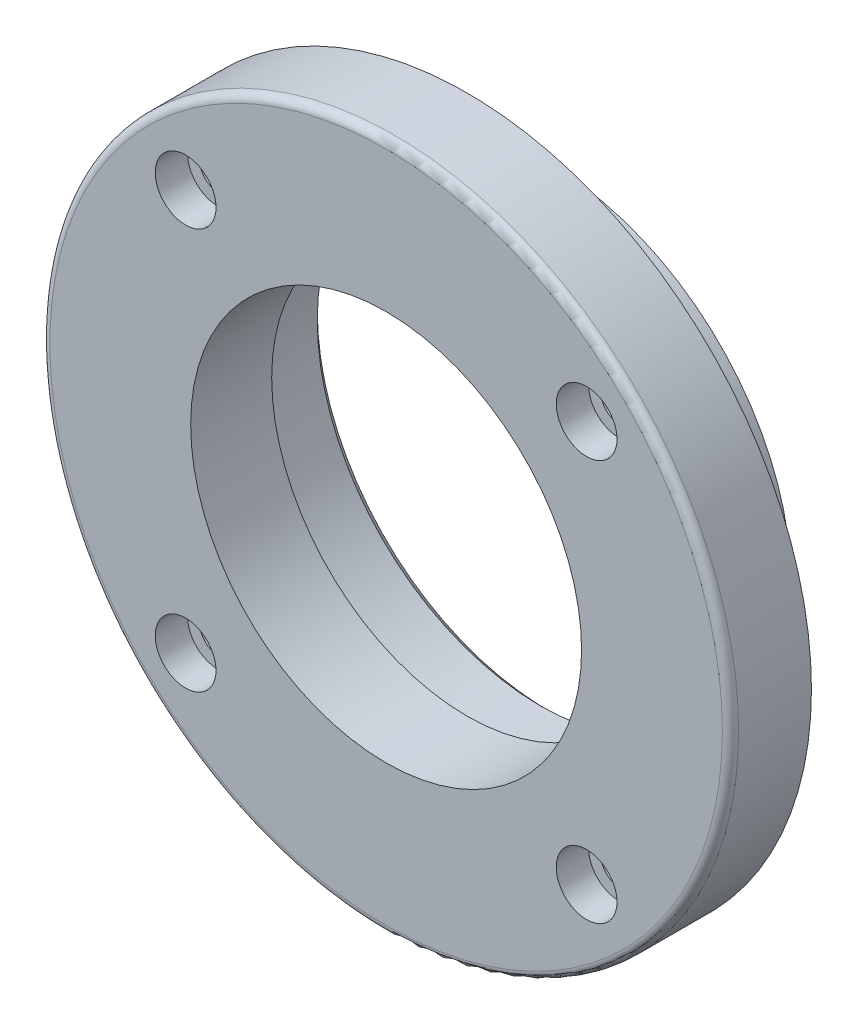
SolidWorks part; units mm, degrees
ref_plane "Piano frontale" through (0, 0, 0) normal (0, 0, 1) x (1, 0, 0)
ref_plane "Piano superiore" through (0, 0, 0) normal (0, 1, 0) x (1, 0, 0)
ref_plane "Piano destro" through (0, 0, 0) normal (1, 0, 0) x (0, 0, -1)
sketch "Schizzo1" plane through (0, 0, 0) normal (0, 0, 1) x (1, 0, 0)
  line L0 (0, 76.5777) -> (0, 0) construction
  line L1 (-69.6481, 0) -> (61.5529, 0) construction
  circle A0 centre (0, 0) radius 85
  circle A4 centre (0, 0) radius 48.25
  point P4 (0, 85)
  point P25 (0, 0)
  dimension "D1" = 170
  dimension "D5" = 96.5
extrude "Estrusione-Estrusione1" add sketch "Schizzo1" along normal blind 20
sketch "Schizzo2" plane through (0, 0, 0) normal (1, 0, 0) x (0, 0, -1)
  line L0 (0, 0) -> (56.1057, 0) construction
  line L1 (0, 60) -> (20, 60)
  line L3 (20, 60) -> (20, 55)
  line L4 (20, 55) -> (0, 55)
  line L5 (0, 55) -> (0, 60)
  dimension "D1" = 110
  dimension "D2" = 120
  dimension "D3" = 20
revolve "Rivoluzione1" add sketch "Schizzo2" angle 360 about L0
fillet "Raccordo1" radius 2 1 edges at (85, 0, 20)
chamfer "Smusso1" distance 2 angle 45 1 edges at (55, 0, -20)
sketch "Schizzo3" plane through (0, 0, 20) normal (0, 0, 1) x (1, 0, 0)
  line L0 (0, 112.0062) -> (0, -151.4596) construction
  line L1 (0, 0) -> (-18.408, 18.408) construction
  line L2 (-38.8909, 38.8909) -> (-60.1041, 60.1041) construction
  circle A0 centre (0, 0) radius 85 construction
  circle A4 centre (0, 0) radius 55 construction
  point P11 (-49.4975, 49.4975)
  dimension "D1" = 45
hole_wizard "Foro lamato per Vite M8 a testa cilindrica piana-1" positions "Schizzo5" profile "Schizzo4" counterbore size "M8" standard "ISO" end condition through all
sketch "Schizzo5" plane through (0, 0, 20) normal (0, 0, 1) x (1, 0, 0)
  point P0 (-49.4975, 49.4975)
sketch "Schizzo4" plane through (-49.4975, 49.4975, 20) normal (1, 0, 0) x (0, -1, 0)
  line L0 (0, 0) -> (0, 40)
  line L1 (0, 40) -> (4.5, 40)
  line L3 (4.5, 40) -> (4.5, 8)
  line L4 (4.5, 8) -> (7.5, 8)
  line L5 (7.5, 8) -> (7.5, 0)
  line L7 (7.5, 0) -> (0, 0)
  line L11 (0, -6.35) -> (0, 107.95) construction
  dimension "Thru Hole Dia." = 9
  dimension "Thru Hole Depth" = 40
  dimension "C'Bore Dia." = 15
  dimension "C'Bore Depth" = 8
pattern_circular "RipetizioneCircolare1" count 4 over 360 about axis through (0, 0, 0) along (0, 0, 1) of "Foro lamato per Vite M8 a testa cilindrica piana-1"
